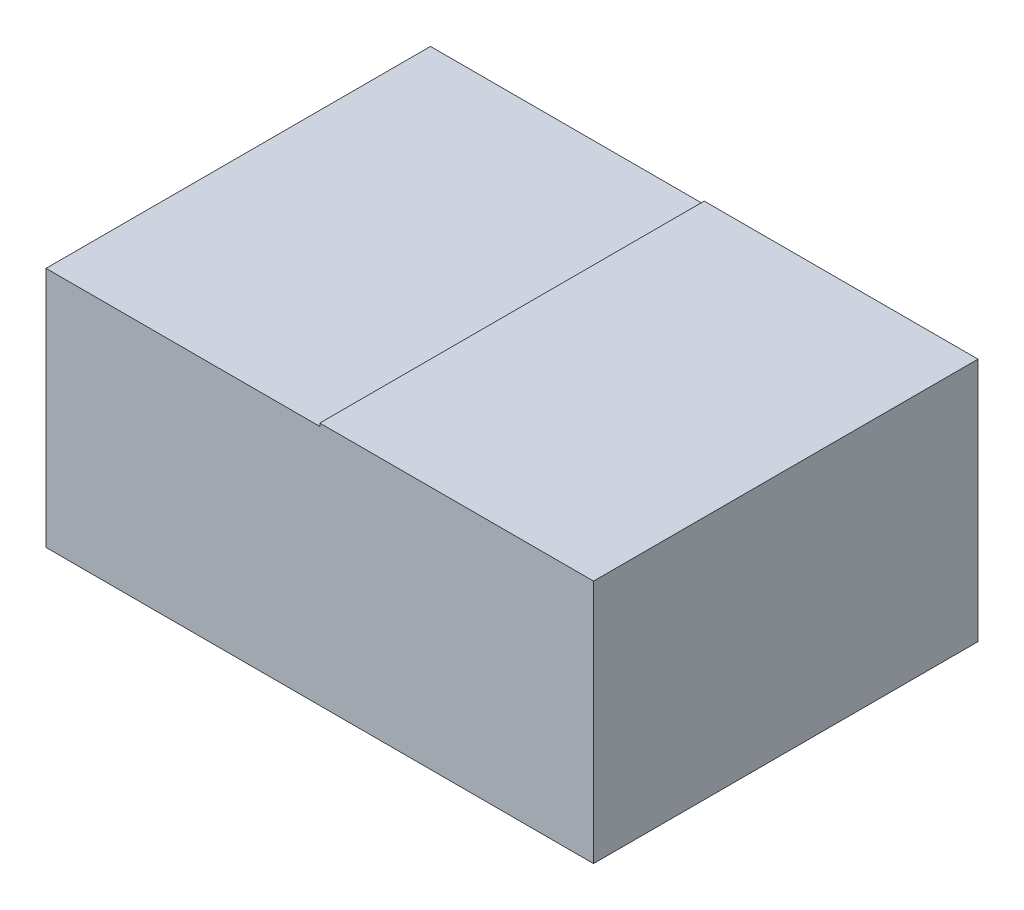
SolidWorks part; units mm, degrees
ref_plane "Front Plane" through (0, 0, 0) normal (0, 0, 1) x (1, 0, 0)
ref_plane "Top Plane" through (0, 0, 0) normal (0, 1, 0) x (1, 0, 0)
ref_plane "Right Plane" through (0, 0, 0) normal (1, 0, 0) x (0, 0, -1)
sketch "Sketch1" plane through (0, 0, 0) normal (0, 1, 0) x (1, 0, 0)
  line L1 (0, 0) -> (18.8, 0)
  line L2 (0, 0) -> (0, 13.2)
  line L3 (0, 13.2) -> (18.8, 13.2)
  line L4 (18.8, 0) -> (18.8, 13.2)
  dimension "D1" = 18.8
  dimension "D2" = 13.2
extrude "Boss-Extrude1" add sketch "Sketch1" along normal blind 8.4
sketch "Sketch2" plane through (0, 8.4, 0) normal (0, 1, 0) x (1, 0, 0)
  line L0 (18.8, 13.2) -> (0, 13.2) construction
  line L1 (0, 13.2) -> (9.4, 13.2)
  line L2 (0, 13.2) -> (0, 0)
  line L3 (0, 0) -> (9.4, 0)
  line L4 (9.4, 13.2) -> (9.4, 0)
  line L5 (0, 13.2) -> (0, 0) construction
  line L6 (0, 0) -> (18.8, 0) construction
  point P10 (9.4, 0)
extrude "Cut-Extrude1" cut sketch "Sketch2" against normal blind 0.1
